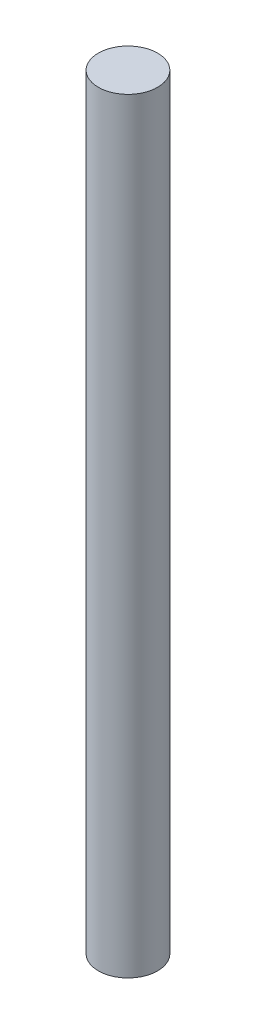
SolidWorks part; units mm, degrees
ref_plane "Plano frontal" through (0, 0, 0) normal (0, 0, 1) x (1, 0, 0)
ref_plane "Plano superior" through (0, 0, 0) normal (0, 1, 0) x (1, 0, 0)
ref_plane "Plano direito" through (0, 0, 0) normal (1, 0, 0) x (0, 0, -1)
sketch "Esboço1" plane through (0, 0, 0) normal (0, 1, 0) x (1, 0, 0)
  circle A0 centre (0, 0) radius 6
  dimension "D1" = 12
extrude "Ressalto-extrusão1" add sketch "Esboço1" along normal blind 155
